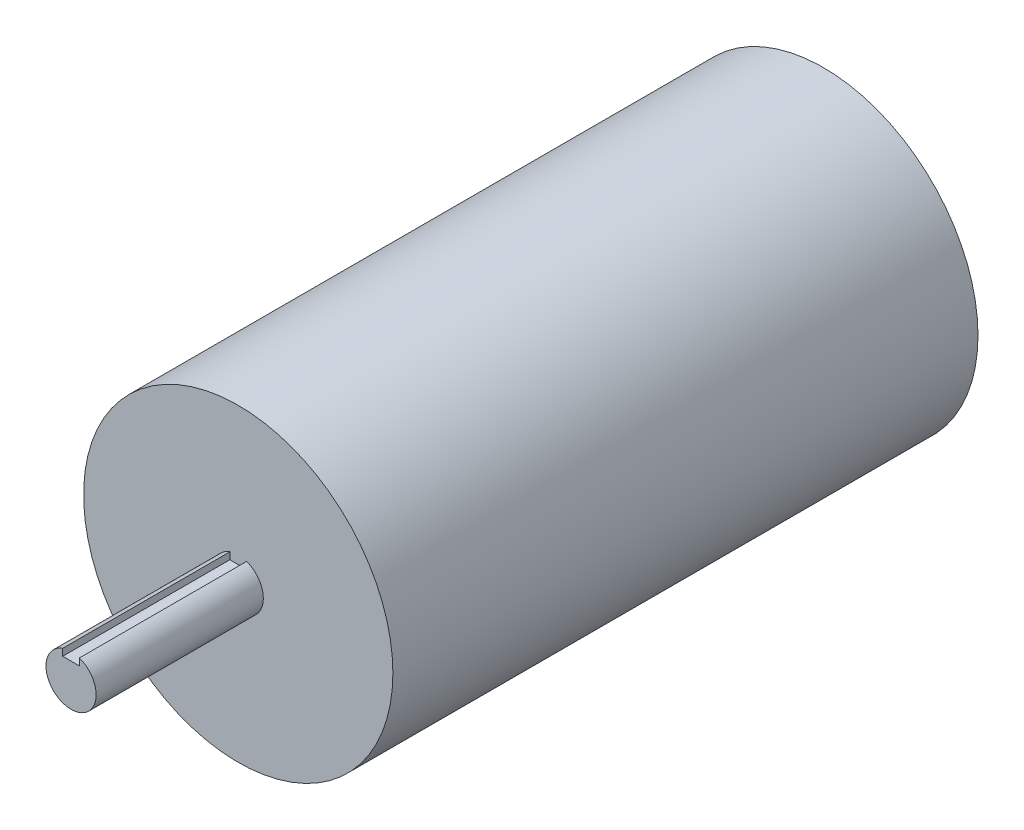
SolidWorks part; units mm, degrees
ref_plane "前视基准面" through (0, 0, 0) normal (0, 0, 1) x (1, 0, 0)
ref_plane "上视基准面" through (0, 0, 0) normal (0, 1, 0) x (1, 0, 0)
ref_plane "右视基准面" through (0, 0, 0) normal (1, 0, 0) x (0, 0, -1)
other "Configuration Table"
sketch "草图1" plane through (0, 0, 0) normal (0, 0, 1) x (1, 0, 0)
  circle A0 centre (0, 0) radius 18.5
extrude "凸台-拉伸1" add sketch "草图1" along normal mid plane 70
sketch "草图2" plane through (0, 0, 35) normal (0, 0, 1) x (1, 0, 0)
  line L0 (-1, 2.8284) -> (-1, 2)
  line L1 (-1, 2) -> (1, 2)
  line L2 (1, 2) -> (1, 2.8284)
  arc A0 (1, 2.8284) -> (-1, 2.8284) centre (0, 0) cw
extrude "凸台-拉伸2" add sketch "草图2" along normal blind 20
